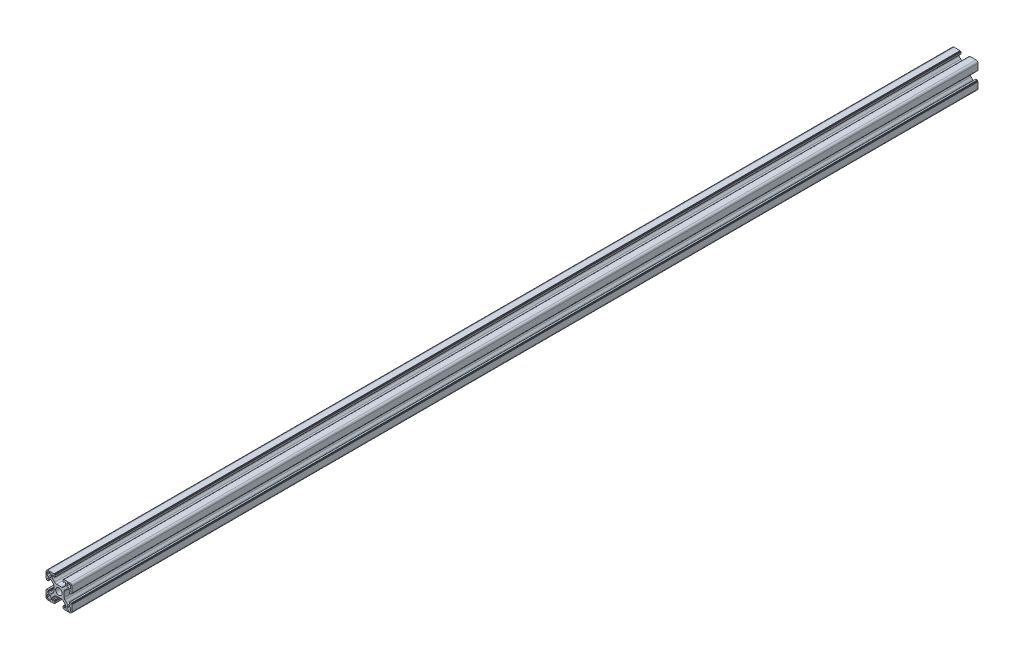
SolidWorks part; units mm, degrees
ref_plane "Спереди" through (0, 0, 0) normal (0, 0, 1) x (1, 0, 0)
ref_plane "Сверху" through (0, 0, 0) normal (0, 1, 0) x (1, 0, 0)
ref_plane "Справа" through (0, 0, 0) normal (1, 0, 0) x (0, 0, -1)
sketch "Эскиз1" plane through (0, 0, 0) normal (0, 0, 1) x (1, 0, 0)
  line L0 (9.6187, 8.8765) -> (6.6187, 5.8765) construction
  line L1 (0.5187, 3.7765) -> (2.4175, 3.7765)
  line L2 (0.5187, -0.2235) -> (10.5187, 9.7765) construction
  line L3 (8.1187, 7.3765) -> (6.6187, 8.8765) construction
  line L4 (3.8317, 4.3623) -> (5.1329, 5.6635)
  line L5 (7.4187, 5.8765) -> (8.8187, 5.8765)
  line L6 (6.6187, 6.6765) -> (6.6187, 8.0765)
  line L7 (8.8187, 8.8765) -> (7.4187, 8.8765)
  line L8 (5.7187, 7.9765) -> (5.7187, 7.0777)
  line L9 (4.2819, 7.8497) -> (4.7622, 8.33)
  line L10 (3.7187, 9.3256) -> (4.2187, 9.3256)
  line L11 (4.1051, 7.7765) -> (3.8187, 7.7765)
  line L12 (5.1158, 8.4765) -> (5.2187, 8.4765)
  line L13 (4.2187, 9.6265) -> (4.2187, 9.3256)
  line L14 (3.5687, 9.1756) -> (3.5687, 8.0265)
  line L15 (9.0187, 9.7765) -> (4.3687, 9.7765)
  line L16 (9.6187, 8.0765) -> (9.6187, 6.6765)
  line L17 (10.5187, 8.2765) -> (10.5187, 3.6265)
  line L18 (9.9177, 2.8265) -> (8.7687, 2.8265)
  line L19 (10.3687, 3.4765) -> (10.0677, 3.4765)
  line L20 (9.2187, 4.3736) -> (9.2187, 4.4765)
  line L21 (8.5187, 3.3629) -> (8.5187, 3.0765)
  line L22 (10.0677, 2.9765) -> (10.0677, 3.4765)
  line L23 (8.5919, 3.5397) -> (9.0722, 4.02)
  line L24 (8.7187, 4.9765) -> (7.8199, 4.9765)
  line L25 (5.1045, 3.0895) -> (6.4057, 4.3907)
  line L26 (4.5187, -0.2235) -> (4.5187, 1.6753)
  line L27 (4.5187, -0.2235) -> (4.5187, -2.1223)
  line L28 (5.1045, -3.5365) -> (6.4057, -4.8377)
  line L29 (6.6187, -7.1235) -> (6.6187, -8.5235)
  line L30 (7.4187, -6.3235) -> (8.8187, -6.3235)
  line L31 (9.6187, -8.5235) -> (9.6187, -7.1235)
  line L32 (8.7187, -5.4235) -> (7.8199, -5.4235)
  line L33 (8.5919, -3.9867) -> (9.0722, -4.4671)
  line L34 (10.0677, -3.4235) -> (10.0677, -3.9235)
  line L35 (8.5187, -3.81) -> (8.5187, -3.5235)
  line L36 (9.2187, -4.8206) -> (9.2187, -4.9235)
  line L37 (10.3687, -3.9235) -> (10.0677, -3.9235)
  line L38 (9.9177, -3.2735) -> (8.7687, -3.2735)
  line L39 (10.5187, -8.7235) -> (10.5187, -4.0735)
  line L40 (8.8187, -9.3235) -> (7.4187, -9.3235)
  line L41 (9.0187, -10.2235) -> (4.3687, -10.2235)
  line L42 (3.5687, -9.6226) -> (3.5687, -8.4735)
  line L43 (4.2187, -10.0735) -> (4.2187, -9.7726)
  line L44 (5.1158, -8.9235) -> (5.2187, -8.9235)
  line L45 (4.1051, -8.2235) -> (3.8187, -8.2235)
  line L46 (3.7187, -9.7726) -> (4.2187, -9.7726)
  line L47 (4.2819, -8.2967) -> (4.7622, -8.7771)
  line L48 (5.7187, -8.4235) -> (5.7187, -7.5247)
  line L49 (3.8317, -4.8093) -> (5.1329, -6.1105)
  line L50 (0.5187, -4.2235) -> (2.4175, -4.2235)
  line L51 (9.6187, -9.3235) -> (6.6187, -6.3235) construction
  line L52 (0.5187, -0.2235) -> (10.5187, -10.2235) construction
  line L53 (8.1187, -7.8235) -> (9.6187, -6.3235) construction
  line L54 (0.5187, -4.2235) -> (-1.3801, -4.2235)
  line L55 (-2.7943, -4.8093) -> (-4.0955, -6.1105)
  line L56 (-6.3813, -6.3235) -> (-7.7813, -6.3235)
  line L57 (-5.5813, -7.1235) -> (-5.5813, -8.5235)
  line L58 (-7.7813, -9.3235) -> (-6.3813, -9.3235)
  line L59 (-4.6813, -8.4235) -> (-4.6813, -7.5247)
  line L60 (-3.2446, -8.2967) -> (-3.7249, -8.7771)
  line L61 (-2.6813, -9.7726) -> (-3.1813, -9.7726)
  line L62 (-3.0678, -8.2235) -> (-2.7813, -8.2235)
  line L63 (-4.0784, -8.9235) -> (-4.1813, -8.9235)
  line L64 (-3.1813, -10.0735) -> (-3.1813, -9.7726)
  line L65 (-2.5313, -9.6226) -> (-2.5313, -8.4735)
  line L66 (-7.9813, -10.2235) -> (-3.3313, -10.2235)
  line L67 (-8.5813, -8.5235) -> (-8.5813, -7.1235)
  line L68 (-9.4813, -8.7235) -> (-9.4813, -4.0735)
  line L69 (-8.8804, -3.2735) -> (-7.7313, -3.2735)
  line L70 (-9.3313, -3.9235) -> (-9.0304, -3.9235)
  line L71 (-8.1813, -4.8206) -> (-8.1813, -4.9235)
  line L72 (-7.4813, -3.81) -> (-7.4813, -3.5235)
  line L73 (-9.0304, -3.4235) -> (-9.0304, -3.9235)
  line L74 (-7.5546, -3.9867) -> (-8.0349, -4.4671)
  line L75 (-7.6813, -5.4235) -> (-6.7825, -5.4235)
  line L76 (-4.0671, -3.5365) -> (-5.3683, -4.8377)
  line L77 (-3.4813, -0.2235) -> (-3.4813, -2.1223)
  line L78 (-8.5813, -9.3235) -> (-5.5813, -6.3235) construction
  line L79 (0.5187, -0.2235) -> (-9.4813, -10.2235) construction
  line L80 (-7.0813, -7.8235) -> (-5.5813, -9.3235) construction
  line L81 (-3.4813, -0.2235) -> (-3.4813, 1.6753)
  line L82 (-4.0671, 3.0895) -> (-5.3683, 4.3907)
  line L83 (-5.5813, 6.6765) -> (-5.5813, 8.0765)
  line L84 (-6.3813, 5.8765) -> (-7.7813, 5.8765)
  line L85 (-8.5813, 8.0765) -> (-8.5813, 6.6765)
  line L86 (-7.6813, 4.9765) -> (-6.7825, 4.9765)
  line L87 (-7.5546, 3.5397) -> (-8.0349, 4.02)
  line L88 (-9.0304, 2.9765) -> (-9.0304, 3.4765)
  line L89 (-7.4813, 3.3629) -> (-7.4813, 3.0765)
  line L90 (-8.1813, 4.3736) -> (-8.1813, 4.4765)
  line L91 (-9.3313, 3.4765) -> (-9.0304, 3.4765)
  line L92 (-8.8804, 2.8265) -> (-7.7313, 2.8265)
  line L93 (-9.4813, 8.2765) -> (-9.4813, 3.6265)
  line L94 (-7.7813, 8.8765) -> (-6.3813, 8.8765)
  line L95 (-7.9813, 9.7765) -> (-3.3313, 9.7765)
  line L96 (-2.5313, 9.1756) -> (-2.5313, 8.0265)
  line L97 (-3.1813, 9.6265) -> (-3.1813, 9.3256)
  line L98 (-4.0784, 8.4765) -> (-4.1813, 8.4765)
  line L99 (-3.0678, 7.7765) -> (-2.7813, 7.7765)
  line L100 (-2.6813, 9.3256) -> (-3.1813, 9.3256)
  line L101 (-3.2446, 7.8497) -> (-3.7249, 8.33)
  line L102 (-4.6813, 7.9765) -> (-4.6813, 7.0777)
  line L103 (-2.7943, 4.3623) -> (-4.0955, 5.6635)
  line L104 (0.5187, 3.7765) -> (-1.3801, 3.7765)
  line L105 (-11.2454, -0.2235) -> (12.023, -0.2235) construction
  line L106 (-8.5813, 8.8765) -> (-5.5813, 5.8765) construction
  line L107 (0.5187, -12.3099) -> (0.5187, 10.4954) construction
  line L108 (0.5187, -0.2235) -> (-9.4813, 9.7765) construction
  line L109 (-7.0813, 7.3765) -> (-8.5813, 5.8765) construction
  arc A0 (9.6187, 8.0765) -> (8.8187, 8.8765) centre (8.8187, 8.0765) ccw
  arc A1 (7.4187, 8.8765) -> (6.6187, 8.0765) centre (7.4187, 8.0765) ccw
  arc A2 (7.4187, 5.8765) -> (6.6187, 6.6765) centre (7.4187, 6.6765) cw
  arc A3 (9.0187, 9.7765) -> (10.5187, 8.2765) centre (9.0187, 8.2765) cw
  arc A4 (3.7187, 9.3256) -> (3.5687, 9.1756) centre (3.7187, 9.1756) ccw
  arc A5 (4.3687, 9.7765) -> (4.2187, 9.6265) centre (4.3687, 9.6265) ccw
  arc A6 (4.1051, 7.7765) -> (4.2819, 7.8497) centre (4.1051, 8.0265) ccw
  arc A7 (3.8187, 7.7765) -> (3.5687, 8.0265) centre (3.8187, 8.0265) cw
  arc A8 (4.7622, 8.33) -> (5.1158, 8.4765) centre (5.1158, 7.9765) cw
  arc A9 (5.2187, 8.4765) -> (5.7187, 7.9765) centre (5.2187, 7.9765) cw
  arc A10 (3.0187, -0.2235) -> (0.5187, 2.2765) centre (0.5187, -0.2235) ccw
  arc A11 (2.4175, 3.7765) -> (3.8317, 4.3623) centre (2.4175, 5.7765) ccw
  arc A12 (5.7187, 7.0777) -> (5.1329, 5.6635) centre (3.7187, 7.0777) cw
  arc A13 (9.6187, 6.6765) -> (8.8187, 5.8765) centre (8.8187, 6.6765) cw
  arc A14 (9.2187, 4.4765) -> (8.7187, 4.9765) centre (8.7187, 4.4765) ccw
  arc A15 (9.0722, 4.02) -> (9.2187, 4.3736) centre (8.7187, 4.3736) ccw
  arc A16 (8.5187, 3.0765) -> (8.7687, 2.8265) centre (8.7687, 3.0765) ccw
  arc A17 (8.5187, 3.3629) -> (8.5919, 3.5397) centre (8.7687, 3.3629) cw
  arc A18 (10.5187, 3.6265) -> (10.3687, 3.4765) centre (10.3687, 3.6265) cw
  arc A19 (10.0677, 2.9765) -> (9.9177, 2.8265) centre (9.9177, 2.9765) cw
  arc A20 (7.8199, 4.9765) -> (6.4057, 4.3907) centre (7.8199, 2.9765) ccw
  arc A21 (4.5187, 1.6753) -> (5.1045, 3.0895) centre (6.5187, 1.6753) cw
  arc A22 (8.8187, -9.3235) -> (9.6187, -8.5235) centre (8.8187, -8.5235) ccw
  arc A23 (9.6187, -7.1235) -> (8.8187, -6.3235) centre (8.8187, -7.1235) ccw
  arc A24 (6.6187, -7.1235) -> (7.4187, -6.3235) centre (7.4187, -7.1235) cw
  arc A25 (10.5187, -8.7235) -> (9.0187, -10.2235) centre (9.0187, -8.7235) cw
  arc A26 (10.0677, -3.4235) -> (9.9177, -3.2735) centre (9.9177, -3.4235) ccw
  arc A27 (10.5187, -4.0735) -> (10.3687, -3.9235) centre (10.3687, -4.0735) ccw
  arc A28 (8.5187, -3.81) -> (8.5919, -3.9867) centre (8.7687, -3.81) ccw
  arc A29 (8.5187, -3.5235) -> (8.7687, -3.2735) centre (8.7687, -3.5235) cw
  arc A30 (9.0722, -4.4671) -> (9.2187, -4.8206) centre (8.7187, -4.8206) cw
  arc A31 (9.2187, -4.9235) -> (8.7187, -5.4235) centre (8.7187, -4.9235) cw
  arc A32 (0.5187, -2.7235) -> (3.0187, -0.2235) centre (0.5187, -0.2235) ccw
  arc A33 (4.5187, -2.1223) -> (5.1045, -3.5365) centre (6.5187, -2.1223) ccw
  arc A34 (7.8199, -5.4235) -> (6.4057, -4.8377) centre (7.8199, -3.4235) cw
  arc A35 (7.4187, -9.3235) -> (6.6187, -8.5235) centre (7.4187, -8.5235) cw
  arc A36 (5.2187, -8.9235) -> (5.7187, -8.4235) centre (5.2187, -8.4235) ccw
  arc A37 (4.7622, -8.7771) -> (5.1158, -8.9235) centre (5.1158, -8.4235) ccw
  arc A38 (3.8187, -8.2235) -> (3.5687, -8.4735) centre (3.8187, -8.4735) ccw
  arc A39 (4.1051, -8.2235) -> (4.2819, -8.2967) centre (4.1051, -8.4735) cw
  arc A40 (4.3687, -10.2235) -> (4.2187, -10.0735) centre (4.3687, -10.0735) cw
  arc A41 (3.7187, -9.7726) -> (3.5687, -9.6226) centre (3.7187, -9.6226) cw
  arc A42 (5.7187, -7.5247) -> (5.1329, -6.1105) centre (3.7187, -7.5247) ccw
  arc A43 (2.4175, -4.2235) -> (3.8317, -4.8093) centre (2.4175, -6.2235) cw
  arc A44 (-8.5813, -8.5235) -> (-7.7813, -9.3235) centre (-7.7813, -8.5235) ccw
  arc A45 (-6.3813, -9.3235) -> (-5.5813, -8.5235) centre (-6.3813, -8.5235) ccw
  arc A46 (-6.3813, -6.3235) -> (-5.5813, -7.1235) centre (-6.3813, -7.1235) cw
  arc A47 (-7.9813, -10.2235) -> (-9.4813, -8.7235) centre (-7.9813, -8.7235) cw
  arc A48 (-2.6813, -9.7726) -> (-2.5313, -9.6226) centre (-2.6813, -9.6226) ccw
  arc A49 (-3.3313, -10.2235) -> (-3.1813, -10.0735) centre (-3.3313, -10.0735) ccw
  arc A50 (-3.0678, -8.2235) -> (-3.2446, -8.2967) centre (-3.0678, -8.4735) ccw
  arc A51 (-2.7813, -8.2235) -> (-2.5313, -8.4735) centre (-2.7813, -8.4735) cw
  arc A52 (-3.7249, -8.7771) -> (-4.0784, -8.9235) centre (-4.0784, -8.4235) cw
  arc A53 (-4.1813, -8.9235) -> (-4.6813, -8.4235) centre (-4.1813, -8.4235) cw
  arc A54 (-1.9813, -0.2235) -> (0.5187, -2.7235) centre (0.5187, -0.2235) ccw
  arc A55 (-1.3801, -4.2235) -> (-2.7943, -4.8093) centre (-1.3801, -6.2235) ccw
  arc A56 (-4.6813, -7.5247) -> (-4.0955, -6.1105) centre (-2.6813, -7.5247) cw
  arc A57 (-8.5813, -7.1235) -> (-7.7813, -6.3235) centre (-7.7813, -7.1235) cw
  arc A58 (-8.1813, -4.9235) -> (-7.6813, -5.4235) centre (-7.6813, -4.9235) ccw
  arc A59 (-8.0349, -4.4671) -> (-8.1813, -4.8206) centre (-7.6813, -4.8206) ccw
  arc A60 (-7.4813, -3.5235) -> (-7.7313, -3.2735) centre (-7.7313, -3.5235) ccw
  arc A61 (-7.4813, -3.81) -> (-7.5546, -3.9867) centre (-7.7313, -3.81) cw
  arc A62 (-9.4813, -4.0735) -> (-9.3313, -3.9235) centre (-9.3313, -4.0735) cw
  arc A63 (-9.0304, -3.4235) -> (-8.8804, -3.2735) centre (-8.8804, -3.4235) cw
  arc A64 (-6.7825, -5.4235) -> (-5.3683, -4.8377) centre (-6.7825, -3.4235) ccw
  arc A65 (-3.4813, -2.1223) -> (-4.0671, -3.5365) centre (-5.4813, -2.1223) cw
  arc A66 (-7.7813, 8.8765) -> (-8.5813, 8.0765) centre (-7.7813, 8.0765) ccw
  arc A67 (-8.5813, 6.6765) -> (-7.7813, 5.8765) centre (-7.7813, 6.6765) ccw
  arc A68 (-5.5813, 6.6765) -> (-6.3813, 5.8765) centre (-6.3813, 6.6765) cw
  arc A69 (-9.4813, 8.2765) -> (-7.9813, 9.7765) centre (-7.9813, 8.2765) cw
  arc A70 (-9.0304, 2.9765) -> (-8.8804, 2.8265) centre (-8.8804, 2.9765) ccw
  arc A71 (-9.4813, 3.6265) -> (-9.3313, 3.4765) centre (-9.3313, 3.6265) ccw
  arc A72 (-7.4813, 3.3629) -> (-7.5546, 3.5397) centre (-7.7313, 3.3629) ccw
  arc A73 (-7.4813, 3.0765) -> (-7.7313, 2.8265) centre (-7.7313, 3.0765) cw
  arc A74 (-8.0349, 4.02) -> (-8.1813, 4.3736) centre (-7.6813, 4.3736) cw
  arc A75 (-8.1813, 4.4765) -> (-7.6813, 4.9765) centre (-7.6813, 4.4765) cw
  arc A76 (0.5187, 2.2765) -> (-1.9813, -0.2235) centre (0.5187, -0.2235) ccw
  arc A77 (-3.4813, 1.6753) -> (-4.0671, 3.0895) centre (-5.4813, 1.6753) ccw
  arc A78 (-6.7825, 4.9765) -> (-5.3683, 4.3907) centre (-6.7825, 2.9765) cw
  arc A79 (-6.3813, 8.8765) -> (-5.5813, 8.0765) centre (-6.3813, 8.0765) cw
  arc A80 (-4.1813, 8.4765) -> (-4.6813, 7.9765) centre (-4.1813, 7.9765) ccw
  arc A81 (-3.7249, 8.33) -> (-4.0784, 8.4765) centre (-4.0784, 7.9765) ccw
  arc A82 (-2.7813, 7.7765) -> (-2.5313, 8.0265) centre (-2.7813, 8.0265) ccw
  arc A83 (-3.0678, 7.7765) -> (-3.2446, 7.8497) centre (-3.0678, 8.0265) cw
  arc A84 (-3.3313, 9.7765) -> (-3.1813, 9.6265) centre (-3.3313, 9.6265) cw
  arc A85 (-2.6813, 9.3256) -> (-2.5313, 9.1756) centre (-2.6813, 9.1756) cw
  arc A86 (-4.6813, 7.0777) -> (-4.0955, 5.6635) centre (-2.6813, 7.0777) ccw
  arc A87 (-1.3801, 3.7765) -> (-2.7943, 4.3623) centre (-1.3801, 5.7765) cw
  point P0 (0.5187, -0.2235)
  point P9 (0.5187, -0.2235)
  point P40 (9.2187, 3.4765)
  point P93 (4.2187, -8.9235)
  point P144 (4.2187, 8.4765)
  point P152 (9.2187, -3.9235)
  point P153 (0.5187, -4.1478)
  point P154 (0.5187, -0.2235)
  point P189 (-8.1813, -3.9235)
  point P228 (-3.1813, -8.9235)
  point P229 (-3.4056, -0.2235)
  point P230 (0.5187, -0.2235)
  point P268 (-3.1813, 8.4765)
  point P273 (4.4429, -0.2235)
  point P306 (-8.1813, 3.4765)
  point P307 (0.5187, 3.7008)
  point P309 (0.5187, -0.2235)
  dimension "D3" = 5
  dimension "D6" = 2
  dimension "D1" = 2
  dimension "D2" = 6
  dimension "D4" = 4
  dimension "D5" = 0.9
extrude "Бобышка-Вытянуть1" add sketch "Эскиз1" along normal blind 701
